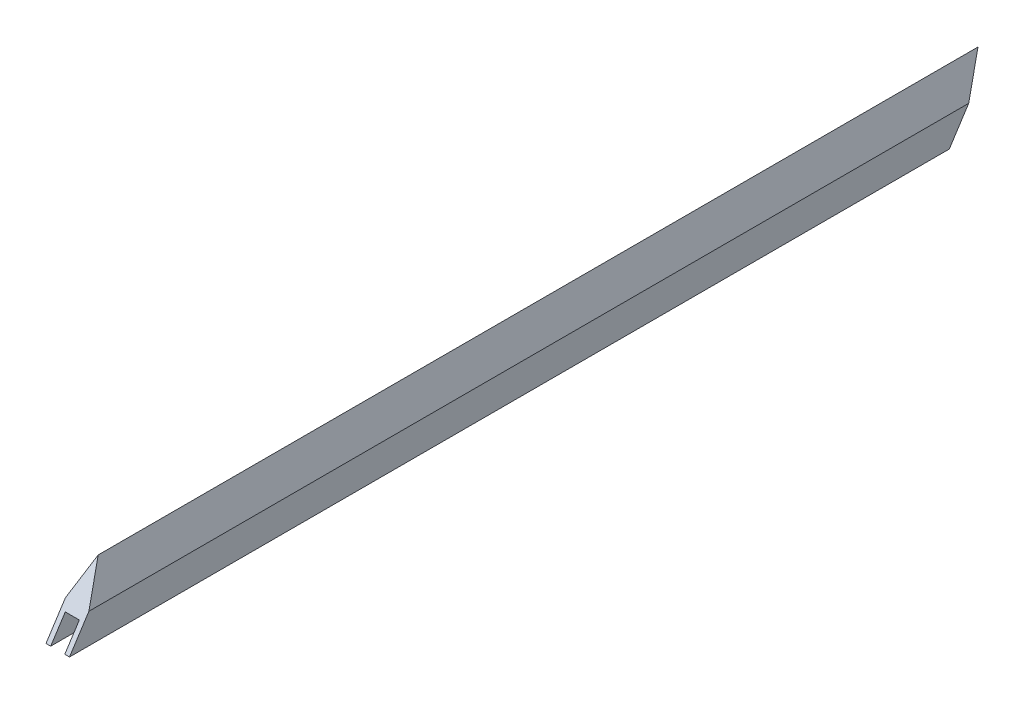
SolidWorks part; units mm, degrees
ref_plane "Front Plane" through (0, 0, 0) normal (0, 0, 1) x (1, 0, 0)
ref_plane "Top Plane" through (0, 0, 0) normal (0, 1, 0) x (1, 0, 0)
ref_plane "Right Plane" through (0, 0, 0) normal (1, 0, 0) x (0, 0, -1)
sketch "Sketch1" plane through (0, 0, 0) normal (0, 0, 1) x (1, 0, 0)
  line L0 (-2.3876, 6.35) -> (2.3876, 6.35) construction
  line L1 (-2.3876, 3.81) -> (2.3876, 3.81)
  line L2 (-2.3876, 3.81) -> (-2.3876, -3.81)
  line L3 (-2.3876, -3.81) -> (2.3876, -3.81) construction
  line L4 (2.3876, 3.81) -> (2.3876, -3.81)
  line L5 (-2.3876, 3.81) -> (2.3876, -3.81) construction
  line L6 (-2.3876, -3.81) -> (2.3876, 3.81) construction
  line L7 (-2.3876, -3.81) -> (-3.9878, -3.81)
  line L9 (-2.3876, 6.35) -> (-3.9878, 6.35) construction
  line L10 (-3.9878, -3.81) -> (-3.9878, 6.35)
  line L11 (2.3876, -3.81) -> (3.9878, -3.81)
  line L13 (2.3876, 6.35) -> (3.9878, 6.35) construction
  line L14 (3.9878, -3.81) -> (3.9878, 6.35)
  line L15 (0, 6.35) -> (0, 17.3609) construction
  line L16 (-3.9878, 6.35) -> (0, 17.3609)
  line L17 (3.9878, 6.35) -> (0, 17.3609)
  point P0 (0, 0)
  dimension "D1" = 7.62
  dimension "D2" = 4.7752
  dimension "D3" = 10.16
  dimension "D4" = 1.6002
  dimension "D5" = 1.6002
  dimension "D6" = 10.16
extrude "Boss-Extrude1" add sketch "Sketch1" along normal blind 313.9694
ref_plane "Plane3" through (0, 142.2174, 219.2468) normal (0, 0.5442, 0.839) x (1, 0, 0)
split "Split1" trim tools "Plane3" bodies to split 101 resulting bodies 103
ref_plane "Plane4" through (0, -1.1283, -1.7395) normal (0, -0.5442, -0.839) x (1, 0, 0)
ref_plane "Plane5" through (0, 5.783, 8.9152) normal (0, -0.5442, -0.839) x (1, 0, 0)
split "Split2" trim tools "Plane5" bodies to split 103 resulting bodies 104
